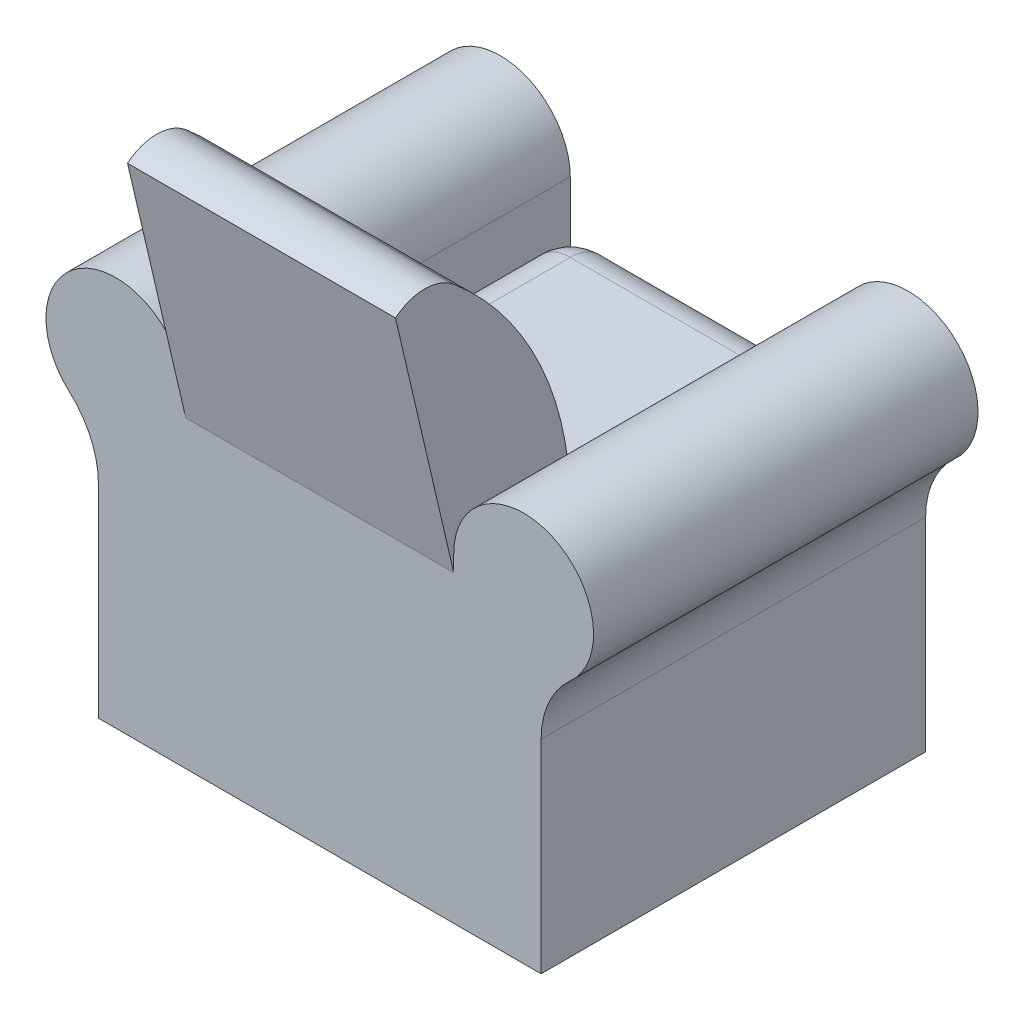
SolidWorks part; units mm, degrees
ref_plane "Front Plane" through (0, 0, 0) normal (0, 0, 1) x (1, 0, 0)
ref_plane "Top Plane" through (0, 0, 0) normal (0, 1, 0) x (1, 0, 0)
ref_plane "Right Plane" through (0, 0, 0) normal (1, 0, 0) x (0, 0, -1)
sketch "Sketch2" plane through (0, 0, 0) normal (0, 1, 0) x (1, 0, 0)
  line L1 (230, -230) -> (-230, -230)
  line L2 (230, -230) -> (230, 230)
  line L3 (230, 230) -> (-230, 230)
  line L4 (-230, -230) -> (-230, 230)
  line L5 (230, -230) -> (-230, 230) construction
  line L6 (230, 230) -> (-230, -230) construction
  point P0 (0, 0)
  dimension "D1" = 460
  dimension "D2" = 460
extrude "Boss-Extrude1" add sketch "Sketch2" along normal blind 350
sketch "Sketch3" plane through (0, 350, 0) normal (0, 1, 0) x (1, 0, 0)
  line L4 (-230, 230) -> (-230, -230)
  line L5 (-230, -230) -> (230, -230)
  line L6 (230, -230) -> (230, 230)
  line L7 (230, 230) -> (-230, 230)
  line L8 (-230, 230) -> (-230, -230)
  line L9 (-230, -230) -> (230, -230)
  line L10 (230, -230) -> (230, 230)
  line L11 (230, 230) -> (-230, 230)
  dimension "D1" = 0
extrude "Boss-Extrude2" add sketch "Sketch3" along normal blind 150 separate body
fillet "Fillet1" radius 70 12 edges at (0, 500, -230) (0, 350, -230) (-230, 425, -230) (-230, 500, 0) (-230, 350, 0) (230, 500, 0) (230, 425, -230) (230, 350, 0) (-230, 425, 230) (0, 500, 230) (230, 425, 230) (0, 350, 230)
sketch "Sketch4" plane through (-230, 0, 0) normal (-1, 0, 0) x (0, 0, 1)
  line L0 (230, 0) -> (230, 521.3192)
  line L1 (530, 950) -> (430, 521.3192)
  line L2 (430, 521.3192) -> (430, 0)
  line L3 (430, 0) -> (230, 0)
  arc A0 (230, 521.3192) -> (430, 950) centre (789.4181, 521.3192) cw
  arc A1 (430, 950) -> (530, 950) centre (480, 890.3646) cw
  point P9 (346.5153, 692.1489)
  point P10 (529.3984, 652.3842)
  point P11 (383.6419, 723.8874)
  point P12 (230, 574.4733)
  point P13 (0, 0)
  point P14 (0, 0)
  point P15 (0, 0)
  point P16 (527.4953, 988.1135)
  point P17 (530, 838.179)
  point P18 (0, 0)
  point P19 (0, 0)
  dimension "D1" = 200
  dimension "D2" = 950
  dimension "D3" = 300
  dimension "D4" = 200
extrude "Boss-Extrude3" add sketch "Sketch4" against normal up to surface (460 mm away) up to face at (230, 175, 0)
sketch "Sketch5" plane through (0, 0, -230) normal (0, 0, -1) x (-1, 0, 0)
  line L0 (230, 0) -> (230, 550)
  line L1 (230, 521.3192) -> (230, 950) construction
  line L2 (380, 348.7539) -> (380, 0)
  line L3 (380, 0) -> (230, 0)
  line L4 (0, 0) -> (0, 583.6627) construction
  line L5 (-380, 0) -> (-230, 0)
  line L6 (-380, 348.7539) -> (-380, 0)
  line L7 (-230, 0) -> (-230, 550)
  arc A0 (230, 550) -> (430, 460.5573) centre (350, 550) cw
  arc A1 (430, 460.5573) -> (380, 348.7539) centre (530, 348.7539) ccw
  arc A2 (-430, 460.5573) -> (-380, 348.7539) centre (-530, 348.7539) cw
  arc A3 (-230, 550) -> (-430, 460.5573) centre (-350, 550) ccw
  dimension "D3" = 120
  dimension "D1" = 550
  dimension "D2" = 150
  dimension "D4" = 200
extrude "Boss-Extrude4" add sketch "Sketch5" against normal up to surface (660 mm away) up to face at (0, 260.6596, 430)
